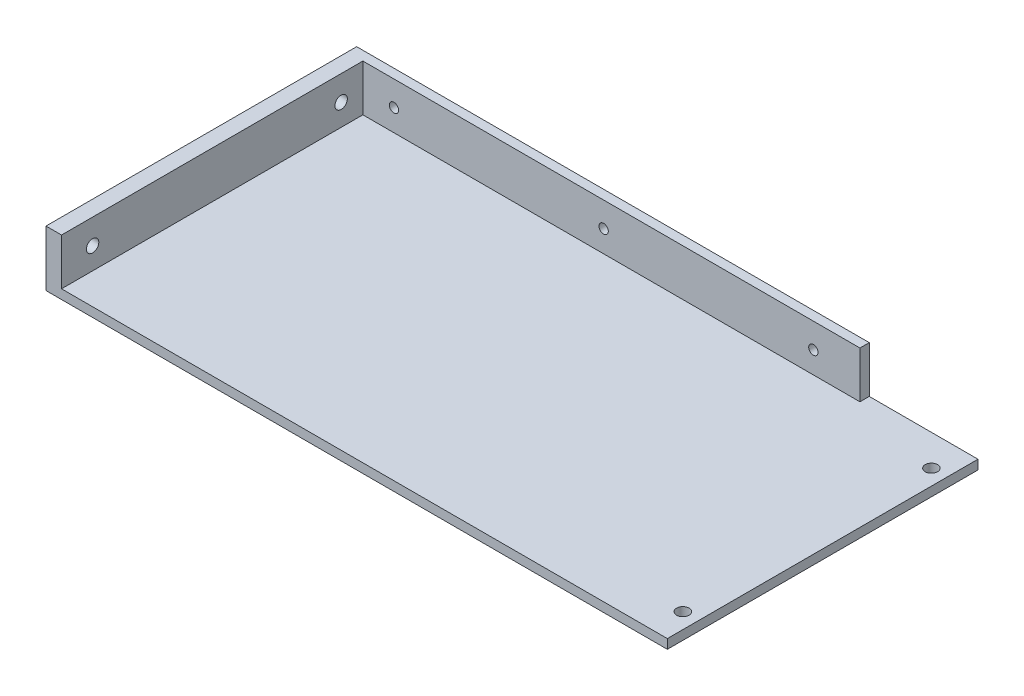
SolidWorks part; units mm, degrees
ref_plane "Front Plane" through (0, 0, 0) normal (0, 0, 1) x (1, 0, 0)
ref_plane "Top Plane" through (0, 0, 0) normal (0, 1, 0) x (1, 0, 0)
ref_plane "Right Plane" through (0, 0, 0) normal (1, 0, 0) x (0, 0, -1)
sketch "Sketch1" plane through (0, 0, 0) normal (0, 1, 0) x (1, 0, 0)
  line L1 (-100, -50) -> (100, -50)
  line L2 (-100, -50) -> (-100, 50)
  line L3 (-100, 50) -> (100, 50)
  line L4 (100, -50) -> (100, 50)
  line L5 (-100, -50) -> (100, 50) construction
  line L6 (-100, 50) -> (100, -50) construction
  point P0 (0, 0)
  dimension "D1" = 100
  dimension "D2" = 200
extrude "Boss-Extrude1" add sketch "Sketch1" along normal blind 3
sketch "Sketch2" plane through (0, 3, 0) normal (0, 1, 0) x (1, 0, 0)
  line L0 (-100, -50) -> (100, -50) construction
  line L1 (-100, 50) -> (-95, 50)
  line L2 (-100, 50) -> (-100, -50)
  line L3 (-100, -50) -> (-95, -50)
  line L4 (-95, 50) -> (-95, -50)
  dimension "D1" = 5
extrude "Boss-Extrude2" add sketch "Sketch2" along normal blind 15
sketch "Sketch3" plane through (-100, 0, 0) normal (-1, 0, 0) x (0, 0, 1)
  line L0 (-50, 0) -> (50, 0) construction
  line L1 (50, 18) -> (50, 0) construction
  circle A0 centre (40, 10) radius 2
  dimension "D1" = 4
  dimension "D2" = 10
  dimension "D3" = 10
extrude "Cut-Extrude1" cut sketch "Sketch3" against normal up to next
pattern_linear "LPattern1" count 2 spacing 80 along (0, 0, -1) of "Cut-Extrude1"
sketch "Sketch4" plane through (0, 3, 0) normal (0, 1, 0) x (1, 0, 0)
  line L0 (100, 50) -> (-95, 50) construction
  line L1 (100, -50) -> (100, 50) construction
  circle A0 centre (95, 40) radius 2
  dimension "D1" = 4
  dimension "D2" = 10
  dimension "D3" = 5
extrude "Cut-Extrude2" cut sketch "Sketch4" against normal up to next
pattern_linear "LPattern2" count 2 spacing 80 along (0, 0, 1) of "Cut-Extrude2"
sketch "Sketch5" plane through (0, 3, 0) normal (0, 1, 0) x (1, 0, 0)
  line L1 (-95, 50) -> (65, 50)
  line L2 (-95, 50) -> (-95, 47)
  line L3 (-95, 47) -> (65, 47)
  line L4 (65, 50) -> (65, 47)
  dimension "D1" = 3
  dimension "D2" = 160
extrude "Boss-Extrude3" add sketch "Sketch5" along normal blind 15
sketch "Sketch6" plane through (0, 0, -50) normal (0, 0, -1) x (-1, 0, 0)
  line L0 (100, 18) -> (100, 0) construction
  line L1 (-100, 0) -> (100, 0) construction
  circle A0 centre (85, 10) radius 1.5
  circle A1 centre (17.5, 10) radius 1.5
  circle A2 centre (-50, 10) radius 1.5
  point P6 (0, 0)
  dimension "D5" = 3
  dimension "D6" = 3
  dimension "D7" = 3
  dimension "D1" = 67.5
  dimension "D2" = 67.5
  dimension "D3" = 15
  dimension "D4" = 10
extrude "Cut-Extrude3" cut sketch "Sketch6" against normal up to next
